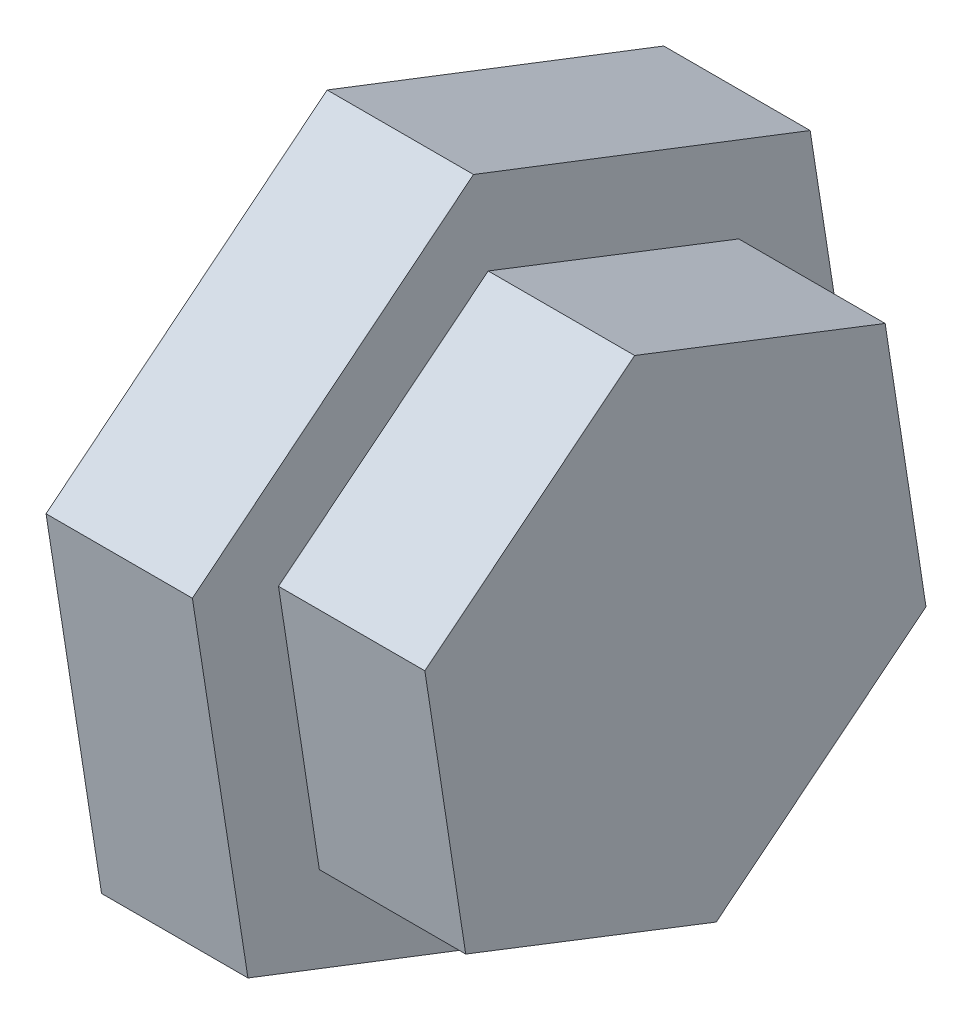
SolidWorks part; units mm, degrees
ref_plane "Front Plane" through (0, 0, 0) normal (0, 0, 1) x (1, 0, 0)
ref_plane "Top Plane" through (0, 0, 0) normal (0, 1, 0) x (1, 0, 0)
ref_plane "Right Plane" through (0, 0, 0) normal (1, 0, 0) x (0, 0, -1)
sketch "Sketch1" plane through (0, 0, 0) normal (1, 0, 0) x (0, 0, -1)
  line L1 (0.1897, -1.2183) -> (1.1499, -0.4449)
  line L2 (1.1499, -0.4449) -> (0.9602, 0.7734)
  line L3 (0.9602, 0.7734) -> (-0.1897, 1.2183)
  line L4 (-0.1897, 1.2183) -> (-1.1499, 0.4449)
  line L5 (-1.1499, 0.4449) -> (-0.9602, -0.7734)
  line L6 (-0.9602, -0.7734) -> (0.1897, -1.2183)
  circle A0 centre (0, 0) radius 1.0678 construction
extrude "Boss-Extrude1" add sketch "Sketch1" along normal blind 0.5
sketch "Sketch2" plane through (0.5, 0, 0) normal (1, 0, 0) x (0, 0, -1)
  line L1 (0.1394, -0.9078) -> (0.8558, -0.3331)
  line L2 (0.8558, -0.3331) -> (0.7164, 0.5746)
  line L3 (0.7164, 0.5746) -> (-0.1394, 0.9078)
  line L4 (-0.1394, 0.9078) -> (-0.8558, 0.3331)
  line L5 (-0.8558, 0.3331) -> (-0.7164, -0.5746)
  line L6 (-0.7164, -0.5746) -> (0.1394, -0.9078)
  circle A0 centre (0, 0) radius 0.7954 construction
  point P1 (-0.7164, -0.5746)
extrude "Boss-Extrude2" add sketch "Sketch2" along normal blind 0.5
